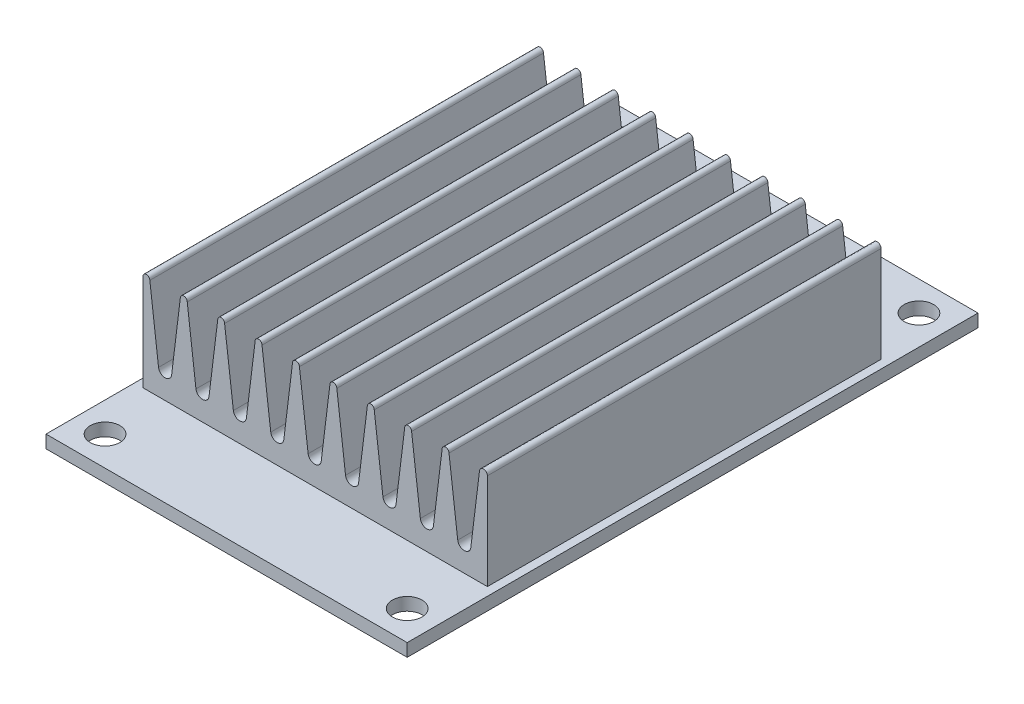
SolidWorks part; units mm, degrees
ref_plane "Alzado" through (0, 0, 0) normal (0, 0, 1) x (1, 0, 0)
ref_plane "Planta" through (0, 0, 0) normal (0, 1, 0) x (1, 0, 0)
ref_plane "Vista lateral" through (0, 0, 0) normal (1, 0, 0) x (0, 0, -1)
sketch "Croquis1" plane through (0, 0, 0) normal (0, 1, 0) x (1, 0, 0)
  line L0 (15.35, -26) -> (15.35, -27.5) construction
  line L1 (15.35, 26) -> (15.35, 27.5) construction
  line L2 (-15.35, 26) -> (-16.85, 26) construction
  line L3 (15.35, 26) -> (16.85, 26) construction
  line L5 (-18.35, 29) -> (18.35, 29)
  line L6 (-18.35, 29) -> (-18.35, -29)
  line L7 (-18.35, -29) -> (18.35, -29)
  line L8 (18.35, 29) -> (18.35, -29)
  line L9 (-18.35, 29) -> (18.35, -29) construction
  line L10 (-18.35, -29) -> (18.35, 29) construction
  circle A0 centre (15.35, 26) radius 1.5
  circle A1 centre (-15.35, 26) radius 1.5
  circle A2 centre (-15.35, -26) radius 1.5
  circle A3 centre (15.35, -26) radius 1.5
  point P10 (0, 0)
  dimension "D2" = 3
  dimension "D3" = 3
  dimension "D4" = 3
  dimension "D5" = 3
  dimension "D7" = 36.7
  dimension "D8" = 58
  dimension "D9" = 3
  dimension "D10" = 1.5
  dimension "D1" = 55
  dimension "D6" = 33.7
extrude "Saliente-Extruir1" add sketch "Croquis1" along normal blind 1.3
sketch "Croquis2" plane through (0, 1.3, 0) normal (0, 1, 0) x (1, 0, 0)
  line L1 (17.5, 20) -> (-17.5, 20)
  line L2 (17.5, 20) -> (17.5, -20)
  line L3 (17.5, -20) -> (-17.5, -20)
  line L4 (-17.5, 20) -> (-17.5, -20)
  line L5 (17.5, 20) -> (-17.5, -20) construction
  line L6 (17.5, -20) -> (-17.5, 20) construction
  point P0 (0, 0)
  dimension "D1" = 35
  dimension "D2" = 40
extrude "Saliente-Extruir2" add sketch "Croquis2" along normal blind 10.2
sketch "Croquis3" plane through (0, 0, 20) normal (0, 0, 1) x (1, 0, 0)
  line L0 (-16.8, 11.1) -> (-15.9145, 3.8879)
  line L1 (-14.5855, 3.8879) -> (-13.7, 11.1)
  line L2 (-15.25, 3.9695) -> (-15.25, 3.3) construction
  line L3 (-18.35, 0) -> (18.35, 0) construction
  line L4 (-17.5, 11.5) -> (-17.5, 1.3) construction
  line L5 (-17.5, 11.5) -> (17.5, 11.5) construction
  line L6 (-13, 11.1) -> (-12.1145, 3.8879)
  line L7 (-10.7855, 3.8879) -> (-9.9, 11.1)
  line L8 (-9.2, 11.1) -> (-8.3145, 3.8879)
  line L9 (-6.9855, 3.8879) -> (-6.1, 11.1)
  line L10 (-5.4, 11.1) -> (-4.5145, 3.8879)
  line L11 (-3.1855, 3.8879) -> (-2.3, 11.1)
  line L12 (-1.6, 11.1) -> (-0.7145, 3.8879)
  line L13 (0.6145, 3.8879) -> (1.5, 11.1)
  line L14 (2.2, 11.1) -> (3.0855, 3.8879)
  line L15 (4.4145, 3.8879) -> (5.3, 11.1)
  line L16 (6, 11.1) -> (6.8855, 3.8879)
  line L17 (8.2145, 3.8879) -> (9.1, 11.1)
  line L18 (9.8, 11.1) -> (10.6855, 3.8879)
  line L19 (12.0145, 3.8879) -> (12.9, 11.1)
  line L20 (13.6, 11.1) -> (14.4855, 3.8879)
  line L21 (15.8145, 3.8879) -> (16.7, 11.1)
  line L22 (17.5, 11.5) -> (17.5, 1.3) construction
  line L23 (17.5, 11.05) -> (17.5, 11.5)
  line L25 (-17.5, 11.5) -> (-17.5, 11.1)
  line L26 (-17.5, 11.5) -> (17.5, 11.5)
  arc A0 (-15.9145, 3.8879) -> (-14.5855, 3.8879) centre (-15.25, 3.9695) ccw
  arc A1 (-16.8, 11.1) -> (-17.5, 11.1) centre (-17.15, 11.1) ccw
  arc A2 (-13, 11.1) -> (-13.7, 11.1) centre (-13.35, 11.1) ccw
  arc A3 (-12.1145, 3.8879) -> (-10.7855, 3.8879) centre (-11.45, 3.9695) ccw
  arc A4 (-9.2, 11.1) -> (-9.9, 11.1) centre (-9.55, 11.1) ccw
  arc A5 (-8.3145, 3.8879) -> (-6.9855, 3.8879) centre (-7.65, 3.9695) ccw
  arc A6 (-5.4, 11.1) -> (-6.1, 11.1) centre (-5.75, 11.1) ccw
  arc A7 (-4.5145, 3.8879) -> (-3.1855, 3.8879) centre (-3.85, 3.9695) ccw
  arc A8 (-1.6, 11.1) -> (-2.3, 11.1) centre (-1.95, 11.1) ccw
  arc A9 (-0.7145, 3.8879) -> (0.6145, 3.8879) centre (-0.05, 3.9695) ccw
  arc A10 (2.2, 11.1) -> (1.5, 11.1) centre (1.85, 11.1) ccw
  arc A11 (3.0855, 3.8879) -> (4.4145, 3.8879) centre (3.75, 3.9695) ccw
  arc A12 (6, 11.1) -> (5.3, 11.1) centre (5.65, 11.1) ccw
  arc A13 (6.8855, 3.8879) -> (8.2145, 3.8879) centre (7.55, 3.9695) ccw
  arc A14 (9.8, 11.1) -> (9.1, 11.1) centre (9.45, 11.1) ccw
  arc A15 (10.6855, 3.8879) -> (12.0145, 3.8879) centre (11.35, 3.9695) ccw
  arc A16 (13.6, 11.1) -> (12.9, 11.1) centre (13.25, 11.1) ccw
  arc A17 (14.4855, 3.8879) -> (15.8145, 3.8879) centre (15.15, 3.9695) ccw
  arc A18 (16.7, 11.1) -> (17.5, 11.05) centre (17.0984, 11.05) cw
  point P11 (20.6643, 10.5799)
  point P22 (17.5, 11.645)
  dimension "D4" = 7
  dimension "D6" = 9
  dimension "D1" = 3.1
  dimension "D2" = 3.3
  dimension "D3" = 0.7
  dimension "D5" = 7
  dimension "D7" = 0.4
  dimension "D8" = 0.45
extrude "Cortar-Extruir1" cut sketch "Croquis3" against normal through all
